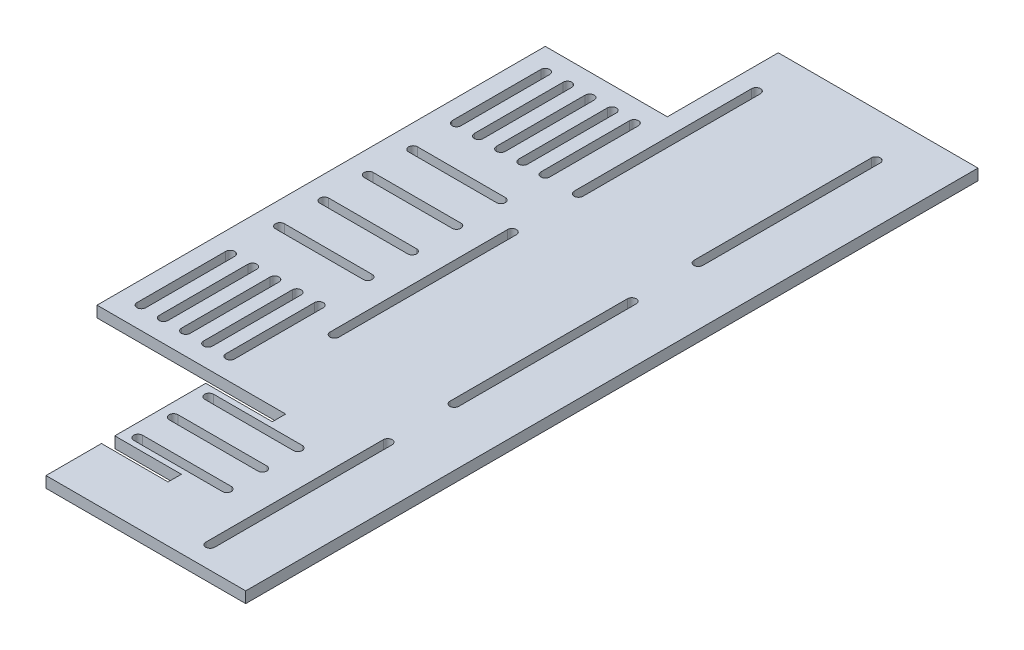
SolidWorks part; units mm, degrees
ref_plane "前视基准面" through (0, 0, 0) normal (0, 0, 1) x (1, 0, 0)
ref_plane "上视基准面" through (0, 0, 0) normal (0, 1, 0) x (1, 0, 0)
ref_plane "右视基准面" through (0, 0, 0) normal (1, 0, 0) x (0, 0, -1)
sketch "Sketch1" plane through (0, 0, 0) normal (0, 1, 0) x (1, 0, 0)
  line L0 (0, 0) -> (0, -43)
  line L1 (0, -43) -> (30, -43)
  line L2 (30, -43) -> (30, -48)
  line L3 (30, -48) -> (0, -48)
  line L5 (0, -73) -> (90, -73)
  line L6 (90, -73) -> (90, 257)
  line L9 (0, 5) -> (30, 5)
  line L10 (30, 5) -> (30, 0)
  line L11 (30, 0) -> (0, 0)
  line L14 (0, -48) -> (0, -73)
  line L16 (-55, 257) -> (-55, 5)
  line L17 (-55, 5) -> (0, 5)
  line L18 (-55, 257) -> (90, 257)
  dimension "D1" = 43
  dimension "D2" = 30
  dimension "D3" = 30
  dimension "D4" = 330
  dimension "D5" = 5
  dimension "D6" = 5
  dimension "D7" = 25
  dimension "D8" = 90
  dimension "D11" = 30
  dimension "D12" = 145
extrude "Boss-Extrude1" add sketch "Sketch1" along normal blind 5
sketch "Sketch2" plane through (0, 5, 0) normal (0, 1, 0) x (1, 0, 0)
  line L0 (-55, 207) -> (0, 207)
  line L1 (-55, 257) -> (-55, 5) construction
  line L2 (0, 207) -> (0, 257)
  line L3 (90, 257) -> (-55, 257) construction
  line L4 (-55, 257) -> (-55, 207)
  line L5 (-55, 257) -> (0, 257)
  dimension "D1" = 50
extrude "Cut-Extrude1" cut sketch "Sketch2" against normal through all
sketch "Sketch3" plane through (0, 5, 0) normal (0, 1, 0) x (1, 0, 0)
  line L0 (90, 263.2654) -> (90, -89.3836) construction
  line L1 (64, 263.2654) -> (64, -89.3836) construction
  line L2 (64, 237) -> (64, 157) construction
  line L3 (66, 237) -> (66, 157)
  line L4 (62, 237) -> (62, 157)
  line L5 (90, 257) -> (0, 257) construction
  line L6 (64, 127) -> (64, 47) construction
  line L7 (66, 127) -> (66, 47)
  line L8 (62, 127) -> (62, 47)
  line L9 (64, 17) -> (64, -63) construction
  line L10 (66, 17) -> (66, -63)
  line L11 (62, 17) -> (62, -63)
  line L12 (0, -73) -> (90, -73) construction
  line L13 (37, 263.2654) -> (37, -89.3836) construction
  line L14 (10, 237) -> (10, 157) construction
  line L15 (8, 237) -> (8, 157)
  line L16 (12, 237) -> (12, 157)
  line L17 (10, 127) -> (10, 47) construction
  line L18 (8, 127) -> (8, 47)
  line L19 (12, 127) -> (12, 47)
  arc A0 (66, 237) -> (62, 237) centre (64, 237) ccw
  arc A1 (62, 157) -> (66, 157) centre (64, 157) ccw
  arc A2 (66, 127) -> (62, 127) centre (64, 127) ccw
  arc A3 (62, 47) -> (66, 47) centre (64, 47) ccw
  arc A4 (66, 17) -> (62, 17) centre (64, 17) ccw
  arc A5 (62, -63) -> (66, -63) centre (64, -63) ccw
  arc A6 (8, 237) -> (12, 237) centre (10, 237) cw
  arc A7 (12, 157) -> (8, 157) centre (10, 157) cw
  arc A8 (8, 127) -> (12, 127) centre (10, 127) cw
  arc A9 (12, 47) -> (8, 47) centre (10, 47) cw
  point P7 (64, 197)
  point P18 (64, 87)
  point P25 (64, -23)
  point P34 (10, 197)
  point P41 (10, 87)
  dimension "D2" = 2
  dimension "D3" = 80
  dimension "D4" = 20
  dimension "D6" = 10
  dimension "D1" = 26
  dimension "D7" = 27
  dimension "D5" = 3
extrude "Cut-Extrude2" cut sketch "Sketch3" against normal through all
sketch "Sketch4" plane through (0, 5, 0) normal (0, 1, 0) x (1, 0, 0)
  line L0 (0, 0) -> (30, 0)
  line L1 (30, 0) -> (30, -1)
  line L2 (30, -1) -> (0, -1)
  line L3 (0, 0) -> (0, -43) construction
  line L4 (0, -1) -> (0, 0)
  line L5 (0, -43) -> (0, -42)
  line L6 (0, -42) -> (30, -42)
  line L7 (30, -42) -> (30, -43)
  line L8 (30, -43) -> (0, -43)
  dimension "D1" = 1
  dimension "D2" = 1
extrude "Cut-Extrude3" cut sketch "Sketch4" against normal through all
sketch "Sketch5" plane through (0, 5, 0) normal (0, 1, 0) x (1, 0, 0)
  line L0 (-13.1599, -21.5) -> (112.4248, -21.5) construction
  line L1 (6, -21.5) -> (46, -21.5) construction
  line L2 (6, -19.5) -> (46, -19.5)
  line L3 (6, -23.5) -> (46, -23.5)
  line L4 (0, -1) -> (0, -42) construction
  line L5 (30, -42) -> (0, -42) construction
  line L12 (6, -5.5) -> (46, -5.5) construction
  line L13 (6, -3.5) -> (46, -3.5)
  line L14 (6, -7.5) -> (46, -7.5)
  line L18 (6, -37.5) -> (46, -37.5) construction
  line L19 (6, -35.5) -> (46, -35.5)
  line L20 (6, -39.5) -> (46, -39.5)
  line L38 (6, -29.5) -> (46, -29.5) construction
  line L39 (6, -27.5) -> (46, -27.5)
  line L40 (6, -31.5) -> (46, -31.5)
  line L41 (6, -13.5) -> (46, -13.5) construction
  line L42 (6, -11.5) -> (46, -11.5)
  line L43 (6, -15.5) -> (46, -15.5)
  line L44 (6, -29.5) -> (46, -29.5) construction
  line L45 (6, -27.5) -> (46, -27.5)
  line L46 (6, -31.5) -> (46, -31.5)
  line L47 (6, -13.5) -> (46, -13.5) construction
  line L48 (6, -11.5) -> (46, -11.5)
  line L49 (6, -15.5) -> (46, -15.5)
  arc A0 (6, -19.5) -> (6, -23.5) centre (6, -21.5) ccw
  arc A1 (46, -23.5) -> (46, -19.5) centre (46, -21.5) ccw
  arc A4 (6, -3.5) -> (6, -7.5) centre (6, -5.5) ccw
  arc A5 (46, -7.5) -> (46, -3.5) centre (46, -5.5) ccw
  arc A8 (6, -35.5) -> (6, -39.5) centre (6, -37.5) ccw
  arc A9 (46, -39.5) -> (46, -35.5) centre (46, -37.5) ccw
  arc A26 (6, -27.5) -> (6, -31.5) centre (6, -29.5) ccw
  arc A27 (46, -31.5) -> (46, -27.5) centre (46, -29.5) ccw
  arc A28 (6, -11.5) -> (6, -15.5) centre (6, -13.5) ccw
  arc A29 (46, -15.5) -> (46, -11.5) centre (46, -13.5) ccw
  point P4 (26, -21.5)
  point P23 (26, -29.5)
  point P30 (26, -5.5)
  point P37 (26, -37.5)
  point P43 (26, -13.5)
  point P50 (26, -29.5)
  point P57 (26, -13.5)
  point P64 (26, -29.5)
  point P71 (26, -13.5)
  point P78 (26, -29.5)
  point P85 (26, -13.5)
  point P92 (26, -29.5)
  point P99 (26, -13.5)
  dimension "D1" = 2
  dimension "D2" = 40
  dimension "D3" = 6
  dimension "D4" = 20.5
  dimension "D5" = 3
  dimension "D6" = 16
  dimension "D8" = 16
  dimension "D7" = 3
extrude "Cut-Extrude4" cut sketch "Sketch5" against normal through all
sketch "Sketch6" plane through (0, 5, 0) normal (0, 1, 0) x (1, 0, 0)
  line L0 (-55, 219.8502) -> (-55, -6.5584) construction
  line L1 (0, 207) -> (0, 257) construction
  line L2 (-45, 219.8502) -> (-45, -6.5584) construction
  line L4 (-45, 197) -> (-45, 157) construction
  line L5 (-43, 197) -> (-43, 157)
  line L6 (-47, 197) -> (-47, 157)
  line L7 (-55, 207) -> (0, 207) construction
  line L8 (-35, 197) -> (-35, 157) construction
  line L9 (-33, 197) -> (-33, 157)
  line L10 (-37, 197) -> (-37, 157)
  line L11 (-25, 197) -> (-25, 157) construction
  line L12 (-23, 197) -> (-23, 157)
  line L13 (-27, 197) -> (-27, 157)
  line L14 (-15, 197) -> (-15, 157) construction
  line L15 (-13, 197) -> (-13, 157)
  line L16 (-17, 197) -> (-17, 157)
  line L17 (-5, 197) -> (-5, 157) construction
  line L18 (-3, 197) -> (-3, 157)
  line L19 (-7, 197) -> (-7, 157)
  line L20 (-55, 5) -> (30, 5) construction
  line L22 (-79.4287, 106) -> (136.0863, 106) construction
  line L23 (-45, 15) -> (-45, 55) construction
  line L24 (-43, 15) -> (-43, 55)
  line L25 (-47, 15) -> (-47, 55)
  line L26 (-35, 15) -> (-35, 55) construction
  line L27 (-33, 15) -> (-33, 55)
  line L28 (-37, 15) -> (-37, 55)
  line L29 (-25, 15) -> (-25, 55) construction
  line L30 (-23, 15) -> (-23, 55)
  line L31 (-27, 15) -> (-27, 55)
  line L32 (-15, 15) -> (-15, 55) construction
  line L33 (-13, 15) -> (-13, 55)
  line L34 (-17, 15) -> (-17, 55)
  line L35 (-5, 15) -> (-5, 55) construction
  line L36 (-3, 15) -> (-3, 55)
  line L37 (-7, 15) -> (-7, 55)
  arc A0 (-43, 197) -> (-47, 197) centre (-45, 197) ccw
  arc A1 (-47, 157) -> (-43, 157) centre (-45, 157) ccw
  arc A2 (-33, 197) -> (-37, 197) centre (-35, 197) ccw
  arc A3 (-37, 157) -> (-33, 157) centre (-35, 157) ccw
  arc A4 (-23, 197) -> (-27, 197) centre (-25, 197) ccw
  arc A5 (-27, 157) -> (-23, 157) centre (-25, 157) ccw
  arc A6 (-13, 197) -> (-17, 197) centre (-15, 197) ccw
  arc A7 (-17, 157) -> (-13, 157) centre (-15, 157) ccw
  arc A8 (-3, 197) -> (-7, 197) centre (-5, 197) ccw
  arc A9 (-7, 157) -> (-3, 157) centre (-5, 157) ccw
  arc A10 (-43, 15) -> (-47, 15) centre (-45, 15) cw
  arc A11 (-47, 55) -> (-43, 55) centre (-45, 55) cw
  arc A12 (-33, 15) -> (-37, 15) centre (-35, 15) cw
  arc A13 (-37, 55) -> (-33, 55) centre (-35, 55) cw
  arc A14 (-23, 15) -> (-27, 15) centre (-25, 15) cw
  arc A15 (-27, 55) -> (-23, 55) centre (-25, 55) cw
  arc A16 (-13, 15) -> (-17, 15) centre (-15, 15) cw
  arc A17 (-17, 55) -> (-13, 55) centre (-15, 55) cw
  arc A18 (-3, 15) -> (-7, 15) centre (-5, 15) cw
  arc A19 (-7, 55) -> (-3, 55) centre (-5, 55) cw
  point P6 (-45, 177)
  point P16 (-35, 177)
  point P23 (-25, 177)
  point P30 (-15, 177)
  point P37 (-5, 177)
  point P49 (-45, 35)
  point P57 (-35, 35)
  point P64 (-25, 35)
  point P71 (-15, 35)
  point P78 (-5, 35)
  dimension "D3" = 2
  dimension "D1" = 55
  dimension "D4" = 40
  dimension "D5" = 10
  dimension "D7" = 40
  dimension "D8" = 101
  dimension "D2" = 10
  dimension "D6" = 5
extrude "Cut-Extrude5" cut sketch "Sketch6" against normal through all
sketch "Sketch7" plane through (0, 5, 0) normal (0, 1, 0) x (1, 0, 0)
  line L0 (-72.6414, 137) -> (13.8532, 137) construction
  line L1 (-72.6414, 157) -> (13.8532, 157) construction
  line L2 (-44.6049, 137) -> (-5, 137) construction
  line L3 (-44.6049, 139) -> (-5, 139)
  line L4 (-44.6049, 135) -> (-5, 135)
  line L5 (-55, 207) -> (-55, 5) construction
  line L6 (-44.6049, 117) -> (-5, 117) construction
  line L7 (-44.6049, 119) -> (-5, 119)
  line L8 (-44.6049, 115) -> (-5, 115)
  line L9 (-44.6049, 97) -> (-5, 97) construction
  line L10 (-44.6049, 99) -> (-5, 99)
  line L11 (-44.6049, 95) -> (-5, 95)
  line L12 (-44.6049, 77) -> (-5, 77) construction
  line L13 (-44.6049, 79) -> (-5, 79)
  line L14 (-44.6049, 75) -> (-5, 75)
  arc A0 (-44.6049, 139) -> (-44.6049, 135) centre (-44.6049, 137) ccw
  arc A1 (-5, 135) -> (-5, 139) centre (-5, 137) ccw
  arc A2 (-44.6049, 119) -> (-44.6049, 115) centre (-44.6049, 117) ccw
  arc A3 (-5, 115) -> (-5, 119) centre (-5, 117) ccw
  arc A4 (-44.6049, 99) -> (-44.6049, 95) centre (-44.6049, 97) ccw
  arc A5 (-5, 95) -> (-5, 99) centre (-5, 97) ccw
  arc A6 (-44.6049, 79) -> (-44.6049, 75) centre (-44.6049, 77) ccw
  arc A7 (-5, 75) -> (-5, 79) centre (-5, 77) ccw
  point P8 (-24.8025, 137)
  point P19 (-24.8025, 117)
  point P26 (-24.8025, 97)
  point P33 (-24.8025, 77)
  dimension "D3" = 2
  dimension "D1" = 0
  dimension "D4" = 10.3951
  dimension "D5" = 2
  dimension "D7" = 60
  dimension "D2" = 20
  dimension "D6" = 4
extrude "Cut-Extrude6" cut sketch "Sketch7" against normal through all
